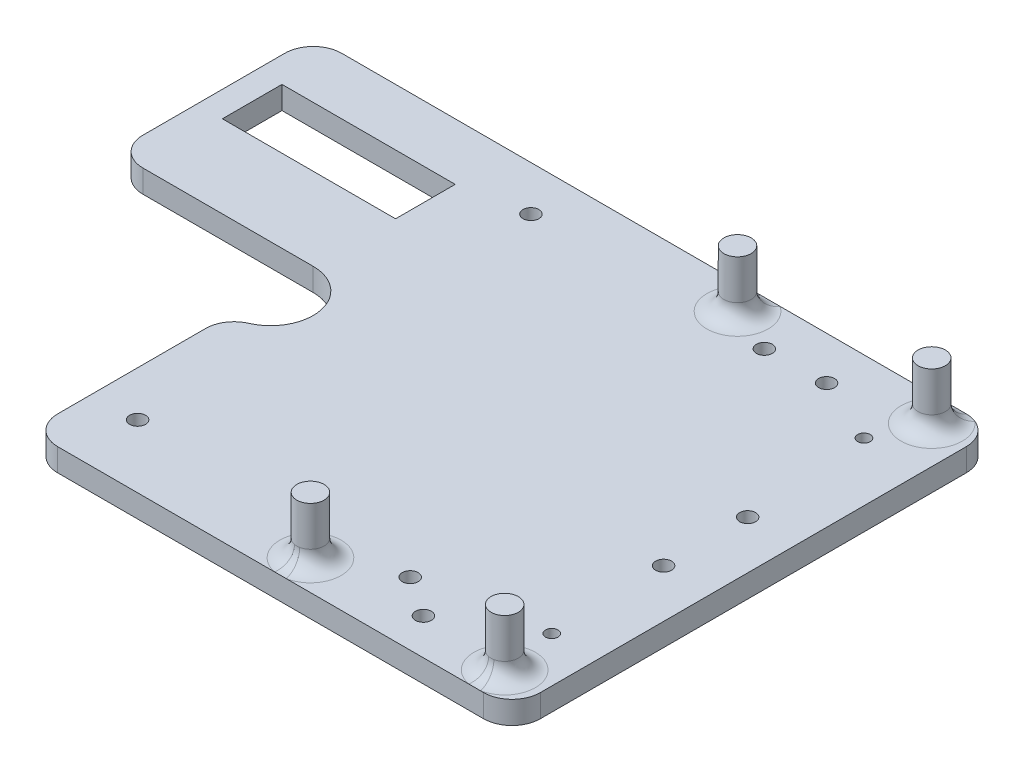
SolidWorks part; units mm, degrees
ref_plane "Front Plane" through (0, 0, 0) normal (0, 0, 1) x (1, 0, 0)
ref_plane "Top Plane" through (0, 0, 0) normal (0, 1, 0) x (1, 0, 0)
ref_plane "Right Plane" through (0, 0, 0) normal (1, 0, 0) x (0, 0, -1)
sketch "Sketch2" plane through (0, 0, 0) normal (0, 1, 0) x (1, 0, 0)
  line L0 (-120, 50) -> (-85, 50)
  line L1 (-85, 0) -> (0, 0)
  line L2 (-120, 50) -> (-120, 85)
  line L3 (-120, 85) -> (0, 85)
  line L4 (0, 0) -> (0, 85)
  line L6 (-85, 0) -> (-85, 35)
  line L8 (-115.5, 75) -> (-85, 75)
  line L9 (-115.5, 75) -> (-115.5, 64.5)
  line L10 (-115.5, 64.5) -> (-85, 64.5)
  line L11 (-85, 75) -> (-85, 64.5)
  arc A0 (-85, 50) -> (-85, 35) centre (-85, 42.5) cw
  dimension "D1" = 120
  dimension "D2" = 85
  dimension "D3" = 35
  dimension "D4" = 85
  dimension "D5" = 35
  dimension "D6" = 30.5
  dimension "D7" = 10.5
  dimension "D8" = 4.5
  dimension "D9" = 10
extrude "Boss-Extrude1" add sketch "Sketch2" along normal blind 4
fillet "Fillet1" radius 5 6 edges at (-120, 2, -50) (-85, 2, -35) (-85, 2, 0) (0, 2, 0) (0, 2, -85) (-120, 2, -85)
sketch "Sketch3" plane through (0, 4, 0) normal (0, 1, 0) x (1, 0, 0)
  line L0 (-5, 85) -> (-115, 85) construction
  circle A0 centre (-6.5862, 80.5) radius 2.4
  circle A1 centre (-40.7862, 80.5) radius 2.4
  circle A2 centre (-40.7862, 5.3001) radius 2.4
  circle A4 centre (-6.5862, 5.3) radius 2.4
  dimension "D1" = 4.8
  dimension "D2" = 4.8
  dimension "D3" = 4.8
  dimension "D4" = 4.8
  dimension "D5" = 75.2
  dimension "D6" = 4.5
  dimension "D7" = 39
  dimension "D8" = 39
extrude "Boss-Extrude2" add sketch "Sketch3" along normal blind 10
sketch "Sketch4" plane through (0, 4, 0) normal (0, 1, 0) x (1, 0, 0)
  line L0 (0, 5) -> (0, 80) construction
  line L1 (-5, 85) -> (-115, 85) construction
  line L2 (-80, 0) -> (-5, 0) construction
  circle A0 centre (-8.5, 50) radius 1.4
  circle A1 centre (-8.5, 35.2) radius 1.4
  circle A2 centre (-8, 15) radius 1.1
  circle A3 centre (-22, 6.4) radius 1.4
  circle A4 centre (-22, 77.4) radius 1.4
  circle A5 centre (-10.3159, 72.2977) radius 1.1
  dimension "D1" = 2.8
  dimension "D2" = 2.8
  dimension "D3" = 2.8
  dimension "D4" = 2.8
  dimension "D5" = 2.2
  dimension "D6" = 2.2
  dimension "D7" = 8.5
  dimension "D8" = 12
  dimension "D10" = 22
  dimension "D12" = 7.8
  dimension "D13" = 15
  dimension "D9" = 35
  dimension "D11" = 71
  dimension "D14" = 8
extrude "Cut-Extrude1" cut sketch "Sketch4" against normal through all both and the other way through all
sketch "Sketch5" plane through (0, 0, 0) normal (0, -1, 0) x (1, 0, 0)
  circle A1 centre (-32.6953, -77.1341) radius 1.4
  circle A2 centre (-73.7953, -77.1341) radius 1.4
  circle A3 centre (-77.0584, -11.1341) radius 1.4
  circle A4 centre (-29.0584, -11.1341) radius 1.4
  dimension "D1" = 2.8
  dimension "D2" = 2.8
  dimension "D3" = 2.8
  dimension "D4" = 2.8
  dimension "D5" = 41.1
  dimension "D7" = 48
  dimension "D8" = 66
extrude "Cut-Extrude2" cut sketch "Sketch5" against normal through all both and the other way through all
fillet "Fillet2" radius 3 1 edges at (-6.5862, 4, -7.7)
fillet "Fillet3" radius 3 1 edges at (-40.7862, 4, -7.7001)
fillet "Fillet4" radius 3 2 edges at (-6.5862, 4, -82.9) (-40.7862, 4, -82.9)
